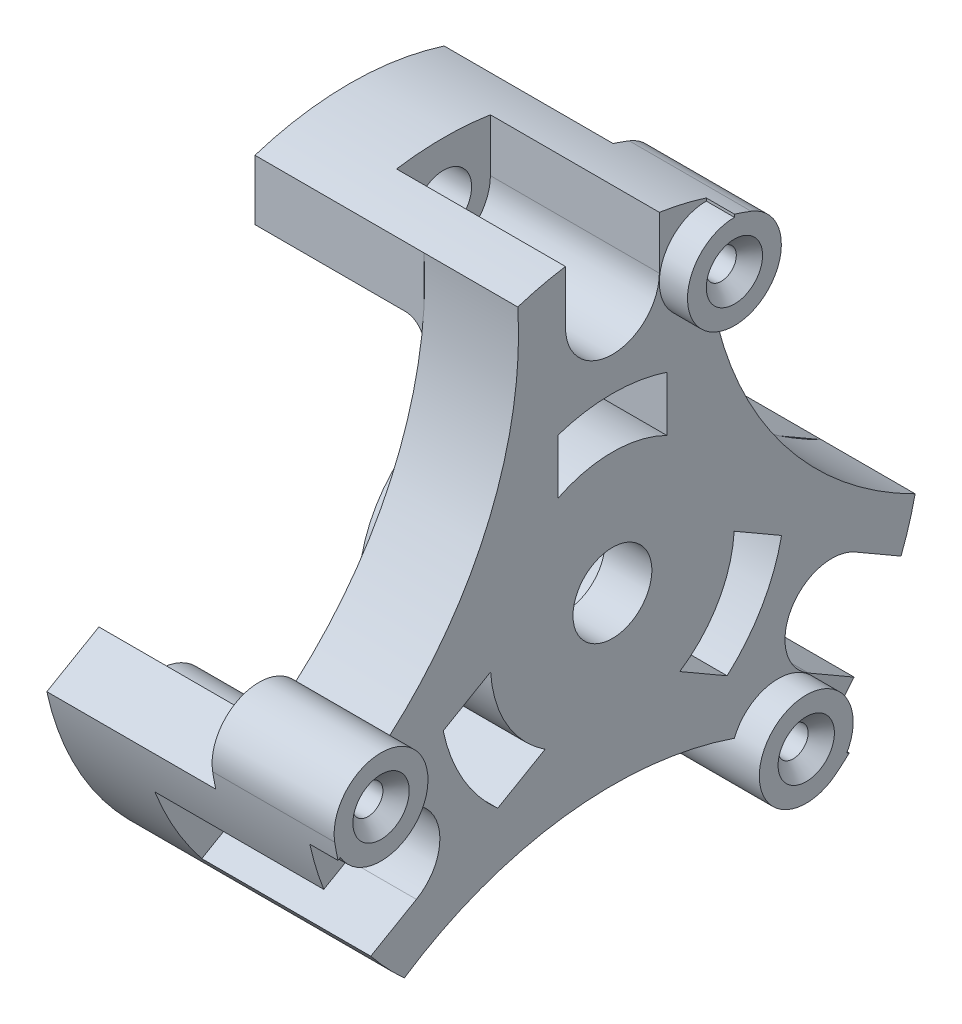
SolidWorks part; units mm, degrees
ref_plane "Front" through (0, 0, 0) normal (0, 0, 1) x (1, 0, 0)
ref_plane "Top" through (0, 0, 0) normal (0, 1, 0) x (1, 0, 0)
ref_plane "Right" through (0, 0, 0) normal (1, 0, 0) x (0, 0, -1)
sketch "草图1" plane through (0, 0, 0) normal (0, 0, 1) x (1, 0, 0)
  line L0 (-65.7429, 0) -> (89.5714, 0) construction
  line L1 (0, 67.1143) -> (0, -71.9143) construction
  line L2 (-7, 6.5) -> (-5, 6.5)
  line L3 (-5, 6.5) -> (-5, 16.5)
  line L4 (-5, 16.5) -> (0, 16.5)
  line L5 (0, 16.5) -> (0, 2.1)
  line L6 (-2.5, 4) -> (-7, 4)
  line L7 (-7, 4) -> (-7, 6.5)
  line L8 (-2.5, 4) -> (-2.5, 2.1)
  line L9 (-2.5, 2.1) -> (0, 2.1)
  dimension "D1" = 4.2
  dimension "D2" = 2.5
  dimension "D3" = 8
  dimension "D4" = 7
  dimension "D5" = 5
  dimension "D6" = 13
  dimension "D7" = 33
revolve "旋转1" add sketch "草图1" angle 360 about L0
sketch "草图2" plane through (-5, 0, 0) normal (-1, 0, 0) x (0, 0, 1)
  line L0 (-23.9515, 0) -> (26.381, 0) construction
  line L1 (0, 44.3891) -> (0, -20.5254) construction
  line L2 (0, 0) -> (-21.2641, -12.2768) construction
  line L3 (0, 0) -> (20.7932, -12.005) construction
  line L4 (0, 0) -> (-61.1055, 35.2793) construction
  line L5 (-5, 31.2128) -> (-5, 9) construction
  line L6 (5, 31.2128) -> (5, 9) construction
  circle A1 centre (-25, 14.4338) radius 20
  point P7 (0, 9)
  point P9 (-7.6795, 4.4338)
  point P17 (-61.1055, 35.2793)
  dimension "D6" = 40
  dimension "D1" = 120
  dimension "D2" = 120
  dimension "D3" = 9
  dimension "D5" = 60
  dimension "D7" = 10
extrude "切除-拉伸1" cut sketch "草图2" against normal blind 10 contours A1
pattern_circular "阵列(圆周)1" count 3 over 360 about axis through (0, 0, 0) along (1, 0, 0) of "切除-拉伸1"
sketch "草图3" plane through (-5, 0, 0) normal (-1, 0, 0) x (0, 0, 1)
  line L0 (0, 18) -> (0, -12.9057) construction
  line L1 (-20.442, 0) -> (20.8303, 0) construction
  line L2 (-2.9, 8.731) -> (-2.9, 5.8172)
  line L4 (2.9, 8.731) -> (2.9, 5.8172)
  arc A0 (2.9, 8.731) -> (-2.9, 8.731) centre (0, 0) ccw
  circle A1 centre (0, 0) radius 6.5 construction
  arc A2 (2.9, 5.8172) -> (-2.9, 5.8172) centre (0, 0) ccw
  dimension "D1" = 9.2
  dimension "D2" = 5.8
extrude "切除-拉伸2" cut sketch "草图3" against normal blind 10
pattern_circular "阵列(圆周)2" count 3 over 360 about axis through (0, 0, 0) along (1, 0, 0) of "切除-拉伸2"
sketch "草图4" plane through (-5, 0, 0) normal (-1, 0, 0) x (0, 0, 1)
  line L0 (-16.7535, 0) -> (15.8993, 0) construction
  line L1 (0, 19.3876) -> (0, -16.6742) construction
  line L2 (-5.0408, 15.7111) -> (-5.0408, 12.5111)
  line L3 (-5.0408, 12.5111) -> (-2.6196, 12.5111)
  line L4 (5.0408, 12.5111) -> (5.0408, 15.7111)
  line L5 (2.6196, 12.5111) -> (5.0408, 12.5111)
  circle A0 centre (0, 0) radius 13.5 construction
  arc A1 (5.0408, 15.7111) -> (-5.0408, 15.7111) centre (0, 0) ccw construction
  arc A2 (5.0408, 15.7111) -> (-5.0408, 15.7111) centre (0, 0) ccw
  circle A3 centre (0, 13.5) radius 1.5
  arc A4 (-2.6196, 12.5111) -> (2.6196, 12.5111) centre (0, 13.5) ccw
  dimension "D1" = 27
  dimension "D2" = 3
  dimension "D4" = 5.6
  dimension "D3" = 3.2
extrude "凸台-拉伸1" add sketch "草图4" along normal blind 9
pattern_circular "阵列(圆周)3" count 3 over 360 about axis through (0, 0, 0) along (1, 0, 0) of "凸台-拉伸1"
sketch "草图5" plane through (-14, 0, 0) normal (-1, 0, 0) x (0, 0, 1)
  line L0 (-16.1323, 0) -> (16.637, 0) construction
  line L1 (0, 17.8058) -> (0, -12.3621) construction
  line L2 (-3.05, 13.6) -> (3.05, 13.6)
  line L3 (-3.05, 13.6) -> (-3.05, 9.2908)
  line L4 (-3.05, 9.2908) -> (3.05, 9.2908)
  line L5 (3.05, 13.6) -> (3.05, 9.2908)
  point P10 (0, 9.2908)
  point P11 (0, 13.6)
  dimension "D1" = 13.6
  dimension "D2" = 6.1
extrude "切除-拉伸3" cut sketch "草图5" against normal blind 1.5 contours L4 L5 L2 L3
pattern_circular "阵列(圆周)4" count 3 over 360 about axis through (0, 0, 0) along (1, 0, 0) of "切除-拉伸3"
sketch "草图6" plane through (0, 0, 0) normal (1, 0, 0) x (0, 0, -1)
  line L0 (-17.245, 0) -> (20.4566, 0) construction
  line L1 (0, 20.1005) -> (0, -14.3306) construction
  line L2 (-2.5, 16.3095) -> (-2.5, 13.5)
  line L3 (2.5, 16.3095) -> (2.5, 13.5)
  circle A0 centre (0, 0) radius 13.5 construction
  arc A1 (5.0408, 15.7111) -> (-5.0408, 15.7111) centre (0, 0) ccw construction
  arc A3 (2.5, 16.3095) -> (-2.5, 16.3095) centre (0, 0) ccw
  arc A4 (-2.5, 13.5) -> (2.5, 13.5) centre (0, 13.5) ccw
  dimension "D1" = 27
  dimension "D3" = 5
  dimension "D2" = 5
extrude "切除-拉伸4" cut sketch "草图6" against normal blind 9
pattern_circular "阵列(圆周)5" count 3 over 360 about axis through (0, 0, 0) along (1, 0, 0) of "切除-拉伸4"
sketch "草图7" plane through (-5, 0, 0) normal (-1, 0, 0) x (0, 0, 1)
  line L0 (0, 19.1221) -> (0, -13.8647) construction
  line L1 (16.0973, 0) -> (-17.961, 0) construction
  line L2 (-5, 15.5767) -> (-5, 15.7242)
  arc A1 (-5.8929, 15.4118) -> (-5, 15.5767) centre (-5, 13.0767) ccw
  circle A5 centre (0, 0) radius 14 construction
  arc A6 (-2.5, 16.3095) -> (-5.0408, 15.7111) centre (0, 0) ccw construction
  arc A7 (-5, 15.7242) -> (-5.8929, 15.4118) centre (0, 0) ccw
  point P7 (-5, 13.0767)
  dimension "D1" = 28
  dimension "D3" = 5
  dimension "D2" = 5
extrude "凸台-拉伸2" add sketch "草图7" against normal blind 6.5 contours A1 L2 A7
sketch "草图9" plane through (1.5, 0, 0) normal (1, 0, 0) x (0, 0, -1)
  line L0 (0, 17.5729) -> (0, -10.6538) construction
  line L1 (-14.0745, 0) -> (16.4041, 0) construction
  circle A0 centre (0, 0) radius 14 construction
  circle A1 centre (5, 13.0767) radius 0.8
  dimension "D1" = 1.6
extrude "切除-拉伸7" cut sketch "草图9" against normal blind 6.4 contours A1
chamfer "倒角3" distance 0.7 angle 45 1 edges at (1.5, 13.0767, -5.8)
pattern_circular "阵列(圆周)8" count 3 over 360 about axis through (0, 0, 0) along (1, 0, 0) of "凸台-拉伸2", "切除-拉伸7", "倒角3"
fillet "圆角2" radius 1 3 edges at (-5, 12.5111, 3.8302) (-5, 10.7, 0) (-5, 12.5111, -3.8302)
fillet "圆角3" radius 1 6 edges at (-5, -9.5726, -8.9199) (-5, -5.35, -9.2665) (-5, -2.9385, -12.7501) (-5, -2.9385, 12.7501) (-5, -5.35, 9.2665) (-5, -9.5726, 8.9199)
chamfer "倒角4" distance 0.3 angle 45 1 edges at (-7, 0, 4)
